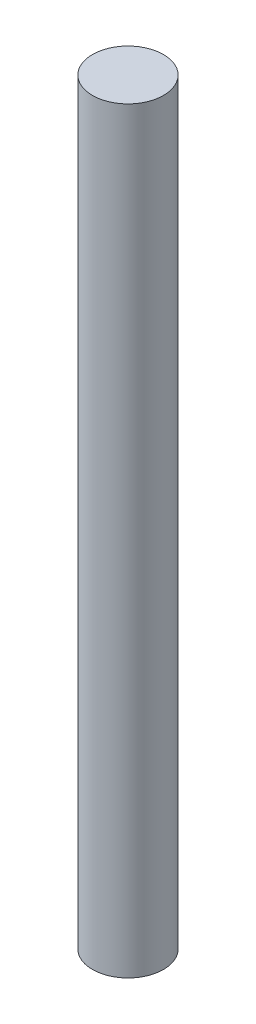
SolidWorks part; units mm, degrees
ref_plane "正面" through (0, 0, 0) normal (0, 0, 1) x (1, 0, 0)
ref_plane "平面" through (0, 0, 0) normal (0, 1, 0) x (1, 0, 0)
ref_plane "右側面" through (0, 0, 0) normal (1, 0, 0) x (0, 0, -1)
sketch "ｽｹｯﾁ1" plane through (0, 0, 0) normal (0, 1, 0) x (1, 0, 0)
  circle A0 centre (0, 0) radius 1.5
  dimension "D1" = 3
extrude "ﾎﾞｽ - 押し出し1" add sketch "ｽｹｯﾁ1" along normal blind 32
